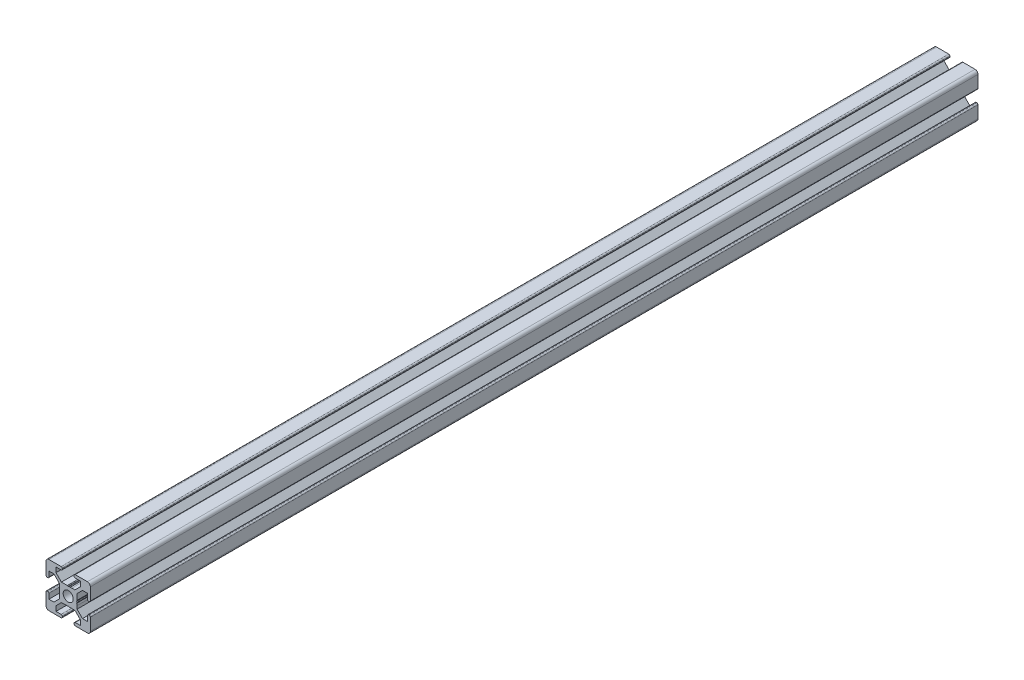
SolidWorks part; units mm, degrees
material "1060 合金"
ref_plane "前视基准面" through (0, 0, 0) normal (0, 0, 1) x (1, 0, 0)
ref_plane "上视基准面" through (0, 0, 0) normal (0, 1, 0) x (1, 0, 0)
ref_plane "右视基准面" through (0, 0, 0) normal (1, 0, 0) x (0, 0, -1)
sketch "草图1" plane through (0, 0, 0) normal (1, 0, 0) x (0, 0, -1)
  line L0 (0, 0) -> (600, 0)
  dimension "D1" = 600
other "铝型材 30 X 30 X R2(1)"
ref_plane "基准面4" through (0, 0, 0) normal (0, 0, -1) x (0, 1, 0)
sketch "草图11" plane through (0, 0, 0) normal (0, 0, -1) x (0, 1, 0)
  line L0 (-15, -4.8) -> (-15, -13)
  line L1 (-13, -15) -> (-4.8, -15)
  line L2 (-4, -14.2) -> (-4, -13.8)
  line L3 (-4.8, -13) -> (-8.25, -13)
  line L4 (-8.25, -13) -> (-8.25, -9.6642)
  line L5 (-8.25, -9.6642) -> (-4.5858, -6)
  line L6 (-4.5858, -6) -> (-0.6536, -6)
  line L7 (-0.4036, -5.933) -> (0, -5.7)
  line L8 (0, -5.7) -> (0.4036, -5.933)
  line L9 (0.9036, -5.933) -> (1.2189, -5.751)
  line L10 (1.2189, -5.751) -> (2.5, -6)
  line L11 (2.5, -6) -> (4.5858, -6)
  line L12 (4.5858, -6) -> (8.25, -9.6642)
  line L13 (8.25, -9.6642) -> (8.25, -13)
  line L14 (8.25, -13) -> (4.8, -13)
  line L15 (4, -13.8) -> (4, -14.2)
  line L16 (4.8, -15) -> (13, -15)
  line L17 (15, -13) -> (15, -4.8)
  line L18 (14.2, -4) -> (13.8, -4)
  line L19 (13, -4.8) -> (13, -8.25)
  line L20 (13, -8.25) -> (9.6642, -8.25)
  line L21 (9.6642, -8.25) -> (6, -4.5858)
  line L22 (6, -4.5858) -> (6, -0.6536)
  line L23 (5.933, -0.4036) -> (5.7, 0)
  line L24 (5.7, 0) -> (5.933, 0.4036)
  line L25 (5.933, 0.9036) -> (5.751, 1.2189)
  line L26 (5.751, 1.2189) -> (6, 2.5)
  line L27 (6, 2.5) -> (6, 4.5858)
  line L28 (6, 4.5858) -> (9.6642, 8.25)
  line L29 (9.6642, 8.25) -> (13, 8.25)
  line L30 (13, 8.25) -> (13, 4.8)
  line L31 (13.8, 4) -> (14.2, 4)
  line L32 (15, 4.8) -> (15, 13)
  line L33 (13, 15) -> (4.8, 15)
  line L34 (4, 14.2) -> (4, 13.8)
  line L35 (4.8, 13) -> (8.25, 13)
  line L36 (8.25, 13) -> (8.25, 9.6642)
  line L37 (8.25, 9.6642) -> (4.5858, 6)
  line L38 (4.5858, 6) -> (0.6536, 6)
  line L39 (0.4036, 5.933) -> (0, 5.7)
  line L40 (0, 5.7) -> (-0.4036, 5.933)
  line L41 (-0.9036, 5.933) -> (-1.2189, 5.751)
  line L42 (-1.2189, 5.751) -> (-2.5, 6)
  line L43 (-2.5, 6) -> (-4.5858, 6)
  line L44 (-4.5858, 6) -> (-8.25, 9.6642)
  line L45 (-8.25, 9.6642) -> (-8.25, 13)
  line L46 (-8.25, 13) -> (-4.8, 13)
  line L47 (-4, 13.8) -> (-4, 14.2)
  line L48 (-4.8, 15) -> (-13, 15)
  line L49 (-15, 13) -> (-15, 4.8)
  line L50 (-14.2, 4) -> (-13.8, 4)
  line L51 (-13, 4.8) -> (-13, 8.25)
  line L52 (-13, 8.25) -> (-9.6642, 8.25)
  line L53 (-9.6642, 8.25) -> (-6, 4.5858)
  line L54 (-6, 4.5858) -> (-6, 0.6536)
  line L55 (-5.933, 0.4036) -> (-5.7, 0)
  line L56 (-5.7, 0) -> (-5.933, -0.4036)
  line L57 (-5.933, -0.9036) -> (-5.751, -1.2189)
  line L58 (-5.751, -1.2189) -> (-6, -2.5)
  line L59 (-6, -2.5) -> (-6, -4.5858)
  line L60 (-6, -4.5858) -> (-9.6642, -8.25)
  line L61 (-9.6642, -8.25) -> (-13, -8.25)
  line L62 (-13, -8.25) -> (-13, -4.8)
  line L63 (-13.8, -4) -> (-14.2, -4)
  arc A0 (-15, -13) -> (-13, -15) centre (-13, -13) ccw
  arc A1 (-4.8, -15) -> (-4, -14.2) centre (-4.8, -14.2) ccw
  arc A2 (-4, -13.8) -> (-4.8, -13) centre (-4.8, -13.8) ccw
  arc A3 (-0.6536, -6) -> (-0.4036, -5.933) centre (-0.6536, -5.5) ccw
  arc A4 (0.4036, -5.933) -> (0.9036, -5.933) centre (0.6536, -5.5) ccw
  arc A5 (4.8, -13) -> (4, -13.8) centre (4.8, -13.8) ccw
  arc A6 (4, -14.2) -> (4.8, -15) centre (4.8, -14.2) ccw
  arc A7 (13, -15) -> (15, -13) centre (13, -13) ccw
  arc A8 (15, -4.8) -> (14.2, -4) centre (14.2, -4.8) ccw
  arc A9 (13.8, -4) -> (13, -4.8) centre (13.8, -4.8) ccw
  arc A10 (6, -0.6536) -> (5.933, -0.4036) centre (5.5, -0.6536) ccw
  arc A11 (5.933, 0.4036) -> (5.933, 0.9036) centre (5.5, 0.6536) ccw
  arc A12 (13, 4.8) -> (13.8, 4) centre (13.8, 4.8) ccw
  arc A13 (14.2, 4) -> (15, 4.8) centre (14.2, 4.8) ccw
  arc A14 (15, 13) -> (13, 15) centre (13, 13) ccw
  arc A15 (4.8, 15) -> (4, 14.2) centre (4.8, 14.2) ccw
  arc A16 (4, 13.8) -> (4.8, 13) centre (4.8, 13.8) ccw
  arc A17 (0.6536, 6) -> (0.4036, 5.933) centre (0.6536, 5.5) ccw
  arc A18 (-0.4036, 5.933) -> (-0.9036, 5.933) centre (-0.6536, 5.5) ccw
  arc A19 (-4.8, 13) -> (-4, 13.8) centre (-4.8, 13.8) ccw
  arc A20 (-4, 14.2) -> (-4.8, 15) centre (-4.8, 14.2) ccw
  arc A21 (-13, 15) -> (-15, 13) centre (-13, 13) ccw
  arc A22 (-15, 4.8) -> (-14.2, 4) centre (-14.2, 4.8) ccw
  arc A23 (-13.8, 4) -> (-13, 4.8) centre (-13.8, 4.8) ccw
  arc A24 (-6, 0.6536) -> (-5.933, 0.4036) centre (-5.5, 0.6536) ccw
  arc A25 (-5.933, -0.4036) -> (-5.933, -0.9036) centre (-5.5, -0.6536) ccw
  arc A26 (-13, -4.8) -> (-13.8, -4) centre (-13.8, -4.8) ccw
  arc A27 (-14.2, -4) -> (-15, -4.8) centre (-14.2, -4.8) ccw
  circle A28 centre (0, 0) radius 3.4
  point P123 (0, 0)
  dimension "D3" = 6.8
  dimension "D1" = 30
  dimension "D2" = 30
